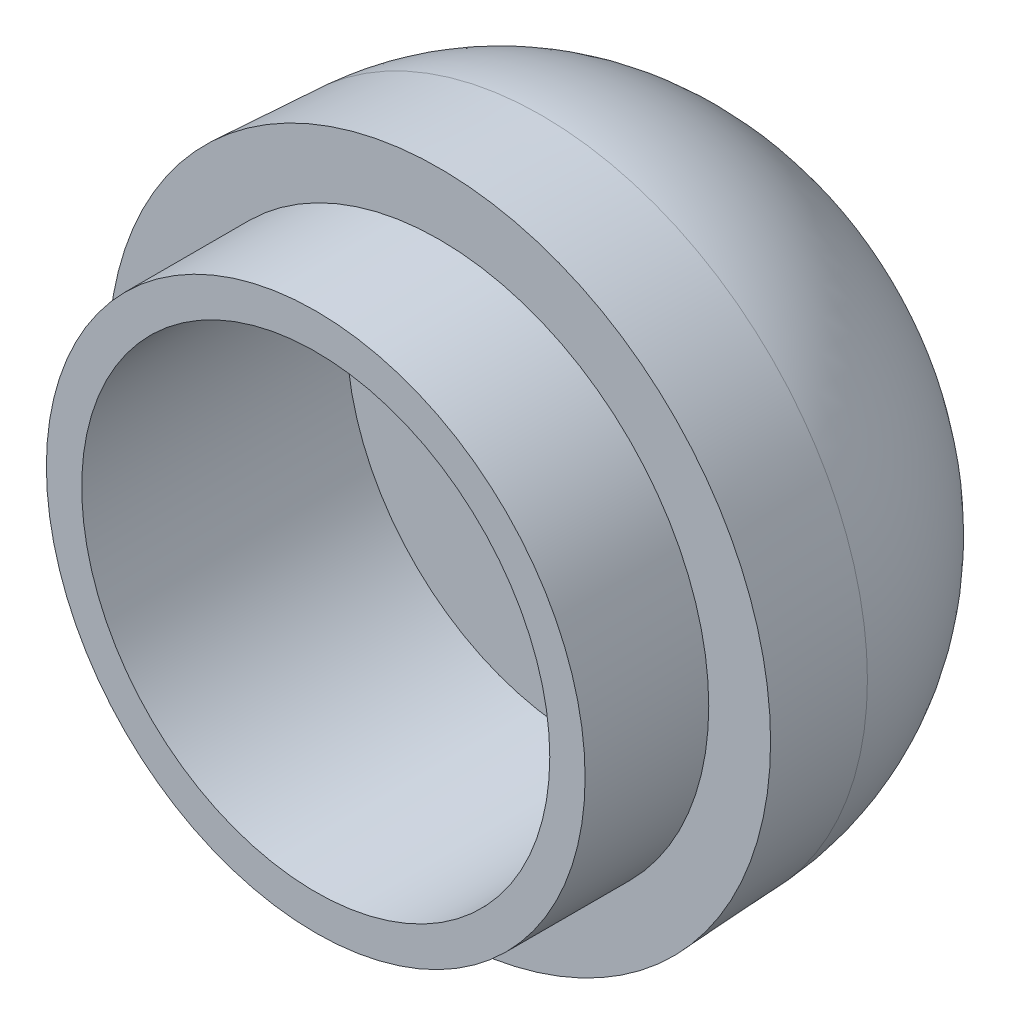
SolidWorks part; units mm, degrees
ref_plane "Plane1" through (0, 0, 0) normal (0, 0, 1) x (1, 0, 0)
ref_plane "Plane2" through (0, 0, 0) normal (0, 1, 0) x (1, 0, 0)
ref_plane "Plane3" through (0, 0, 0) normal (1, 0, 0) x (0, 0, -1)
sketch "Sketch1" plane through (0, 0, 0) normal (0, 0, 1) x (1, 0, 0)
  circle A0 centre (0, 0) radius 4.7625
  dimension "D1" = 9.525
extrude "Base-Extrude" add sketch "Sketch1" against normal blind 5.08 draft 3
fillet "Fillet3" radius 3.81 1 edges at (4.4963, 0, -5.08)
sketch "Sketch2" plane through (0, 0, 0) normal (0, 0, 1) x (1, 0, 0)
  circle A1 centre (0, 0) radius 3.8735
  circle A2 centre (0, 0) radius 3.8735
  dimension "D1" = 0.889
extrude "Boss-Extrude1" add sketch "Sketch2" along normal blind 1.778
sketch "Sketch3" plane through (0, 0, 1.778) normal (0, 0, 1) x (1, 0, 0)
  circle A1 centre (0, 0) radius 3.3655
  circle A2 centre (0, 0) radius 3.3655
  dimension "D1" = 0.508
extrude "Cut-Extrude1" cut sketch "Sketch3" against normal blind 3.81
